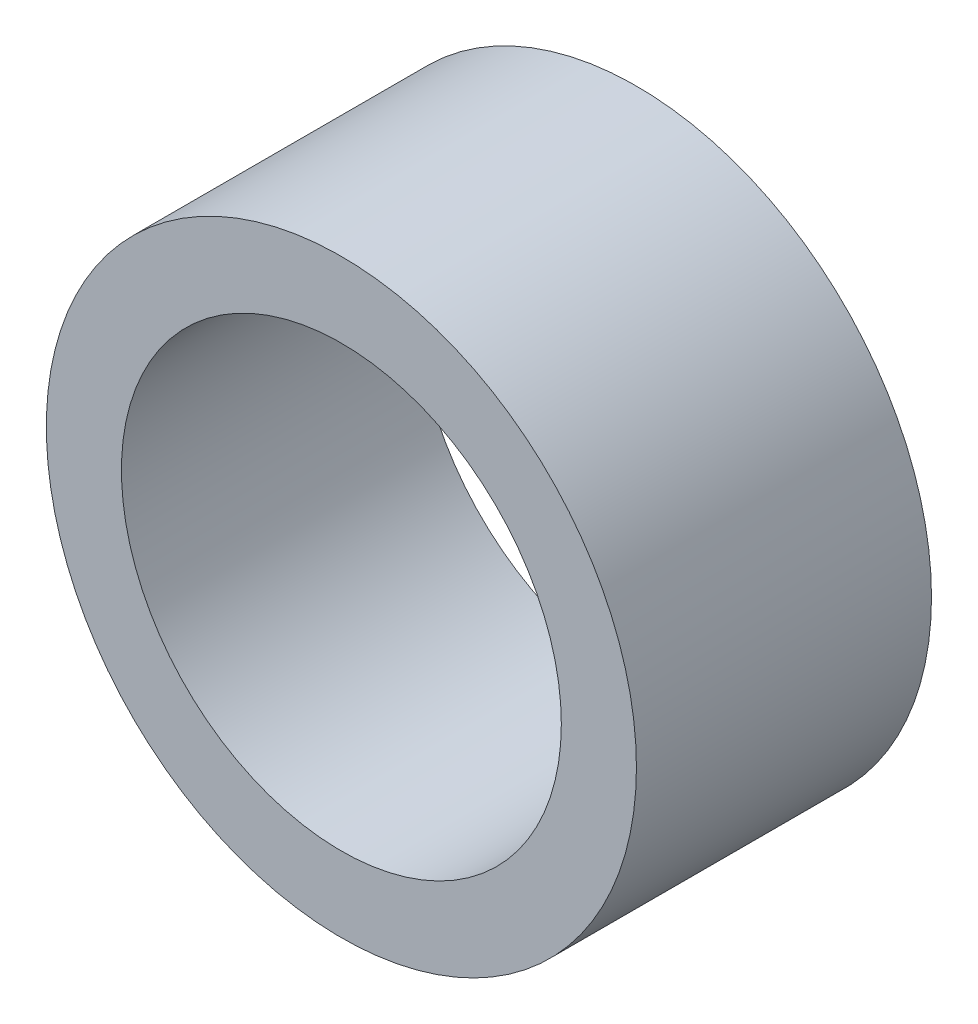
SolidWorks part; units mm, degrees
ref_plane "Front Plane" through (0, 0, 0) normal (0, 0, 1) x (1, 0, 0)
ref_plane "Top Plane" through (0, 0, 0) normal (0, 1, 0) x (1, 0, 0)
ref_plane "Right Plane" through (0, 0, 0) normal (1, 0, 0) x (0, 0, -1)
sketch "Sketch1" plane through (0, 0, 0) normal (0, 0, 1) x (1, 0, 0)
  circle A0 centre (0, 0) radius 5.5
  circle A1 centre (0, 0) radius 4.1
  dimension "D1" = 11
  dimension "D2" = 8.2
extrude "Boss-Extrude1" add sketch "Sketch1" along normal blind 5.5
